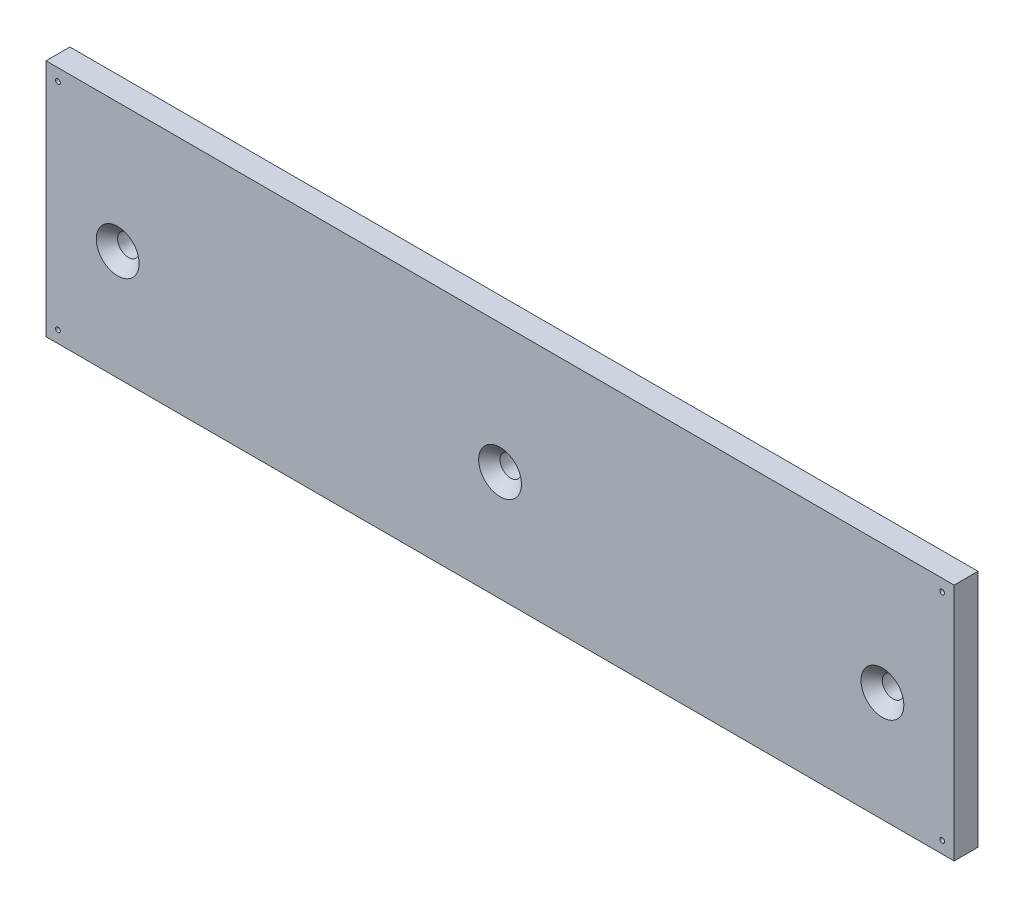
SolidWorks part; units mm, degrees
material "Cedro"
ref_plane "Plano frontal" through (0, 0, 0) normal (0, 0, 1) x (1, 0, 0)
ref_plane "Plano superior" through (0, 0, 0) normal (0, 1, 0) x (1, 0, 0)
ref_plane "Plano direito" through (0, 0, 0) normal (1, 0, 0) x (0, 0, -1)
sketch "Esboço1" plane through (0, 0, 0) normal (0, 0, 1) x (1, 0, 0)
  line L1 (0, 0) -> (190, 0)
  line L2 (0, 0) -> (0, 50)
  line L3 (0, 50) -> (190, 50)
  line L4 (190, 0) -> (190, 50)
  dimension "D1" = 50
  dimension "D2" = 190
extrude "Ressalto-extrusão1" add sketch "Esboço1" along normal blind 5
sketch "Esboço2" plane through (0, 0, 5) normal (0, 0, 1) x (1, 0, 0)
  line L0 (190, 50) -> (0, 50) construction
  line L1 (0, 50) -> (0, 0) construction
  line L2 (190, 0) -> (190, 50) construction
  line L3 (0, 0) -> (190, 0) construction
  line L4 (0, 23) -> (190, 23) construction
  point P0 (2.5, 47.5)
  point P1 (2.5, 2.5)
  point P2 (187.5, 2.5)
  point P3 (187.5, 47.5)
  point P14 (15, 23)
  point P15 (175, 23)
  point P16 (95, 23)
  dimension "D1" = 2.5
  dimension "D2" = 2.5
  dimension "D3" = 2.5
  dimension "D4" = 2.5
  dimension "D5" = 2.5
  dimension "D6" = 2.5
  dimension "D7" = 2.5
  dimension "D8" = 2.5
  dimension "D9" = 27
  dimension "D10" = 15
  dimension "D11" = 15
hole_wizard "Furo de diâmetro Ø1.0 (1)1" positions "3DSketch1" profile "Esboço3" hole size "Ø1.0" standard "Ansi Metric" end condition through all
sketch3d "3DSketch1"
  point P0 (2.5, 47.5, 5)
  point P3 (2.5, 2.5, 5)
  point P6 (187.5, 2.5, 5)
  point P9 (187.5, 47.5, 5)
sketch "Esboço3" plane through (2.5, 47.5, 5) normal (1, 0, 0) x (0, -1, 0)
  line L0 (0, 0) -> (0, 5)
  line L1 (0, 5) -> (0.5, 5)
  line L2 (0.5, 5) -> (0.5, 0)
  line L5 (0.5, 0) -> (0, 0)
  line L11 (0, -6.35) -> (0, 107.95) construction
  dimension "Thru Hole Dia." = 1
  dimension "Thru Hole Depth" = 5
hole_wizard "Escareado para SFHCS M41" positions "3DSketch2" profile "Esboço4" countersink size "M4" standard "Ansi Metric" end condition through all
sketch3d "3DSketch2"
  point P0 (15, 23, 5)
  point P3 (95, 23, 5)
sketch "Esboço4" plane through (15, 23, 5) normal (1, 0, 0) x (0, -1, 0)
  line L0 (0, 0) -> (0, 5)
  line L1 (0, 5) -> (2.25, 5)
  line L2 (2.25, 5) -> (2.25, 2.23)
  line L3 (2.25, 2.23) -> (4.48, 0)
  line L5 (4.48, 0) -> (0, 0)
  line L6 (-2.25, 2.23) -> (-4.48, 0) construction
  line L11 (0, -6.35) -> (0, 107.95) construction
  dimension "Thru Hole Dia." = 4.5
  dimension "Thru Hole Depth" = 5
  dimension "Near C'Sink Dia." = 8.96
  dimension "Near C'Sink Angle" = 90
hole_wizard "Escareado para SFHCS M42" positions "3DSketch3" profile "Esboço5" countersink size "M4" standard "Ansi Metric" end condition through all
sketch3d "3DSketch3"
  point P0 (175, 23, 5)
sketch "Esboço5" plane through (175, 23, 5) normal (1, 0, 0) x (0, -1, 0)
  line L0 (0, 0) -> (0, 5)
  line L1 (0, 5) -> (2.25, 5)
  line L2 (2.25, 5) -> (2.25, 2.23)
  line L3 (2.25, 2.23) -> (4.48, 0)
  line L5 (4.48, 0) -> (0, 0)
  line L6 (-2.25, 2.23) -> (-4.48, 0) construction
  line L11 (0, -6.35) -> (0, 107.95) construction
  dimension "Thru Hole Dia." = 4.5
  dimension "Thru Hole Depth" = 5
  dimension "Near C'Sink Dia." = 8.96
  dimension "Near C'Sink Angle" = 90
